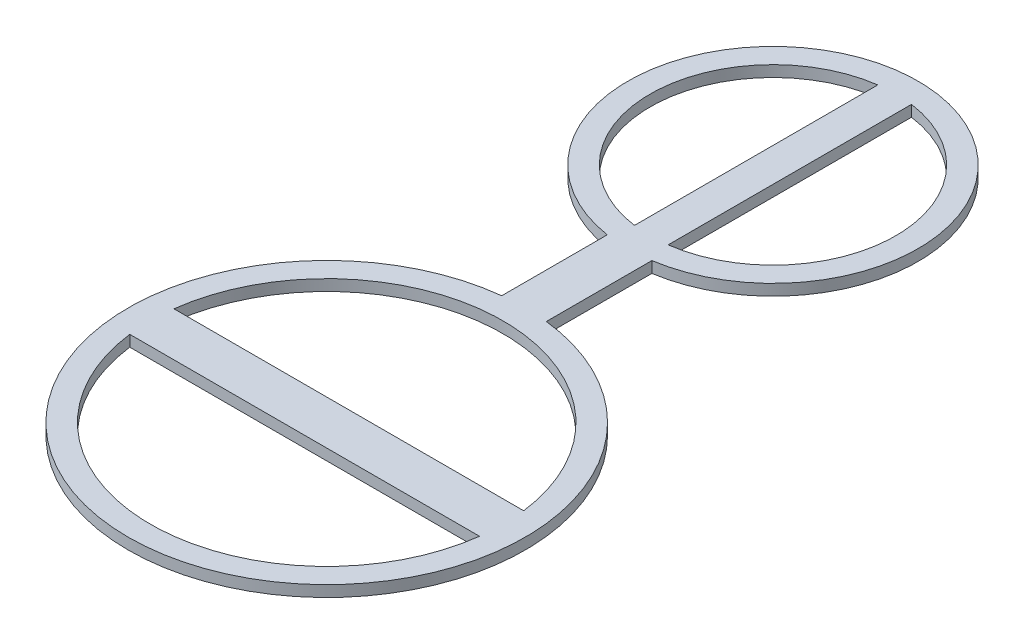
SolidWorks part; units mm, degrees
ref_plane "Front Plane" through (0, 0, 0) normal (0, 0, 1) x (1, 0, 0)
ref_plane "Top Plane" through (0, 0, 0) normal (0, 1, 0) x (1, 0, 0)
ref_plane "Right Plane" through (0, 0, 0) normal (1, 0, 0) x (0, 0, -1)
sketch "Sketch1" plane through (0, 0, 0) normal (0, 1, 0) x (1, 0, 0)
  line L0 (0, 0) -> (79, 0) construction
  line L1 (0, 0) -> (-79, 0) construction
  line L2 (0, 9.9) -> (79, 9.9)
  line L3 (0, 9.9) -> (-79, 9.9)
  line L4 (0, -9.9) -> (79, -9.9)
  line L5 (0, -9.9) -> (-79, -9.9)
  line L6 (0, 0) -> (0, 200) construction
  line L7 (55, 200) -> (-55, 200) construction
  line L8 (-7.55, 255) -> (-7.55, 145)
  line L9 (7.55, 255) -> (7.55, 145)
  line L10 (0, 89) -> (0, 135) construction
  line L11 (10, 88.4364) -> (10, 135)
  line L12 (-10, 88.4364) -> (-10, 135)
  line L13 (-10, 89) -> (-10, 135) construction
  line L14 (10, 89) -> (10, 135) construction
  line L15 (-10, 135) -> (-10, 135.7232)
  line L16 (10, 135) -> (10, 135.7232)
  arc A0 (-78.3772, -9.9) -> (78.3772, -9.9) centre (0, 0) ccw
  circle A1 centre (0, 0) radius 89
  circle A2 centre (0, 0) radius 79 construction
  arc A3 (78.3772, 9.9) -> (-78.3772, 9.9) centre (0, 0) ccw
  arc A4 (7.55, 145.4702) -> (7.55, 254.5298) centre (0, 200) ccw
  arc A5 (10, 135.7232) -> (-10, 135.7232) centre (0, 200) ccw
  arc A8 (-7.55, 254.5298) -> (-7.55, 145.4702) centre (0, 200) ccw
  dimension "D1" = 158
  dimension "D6" = 110.1
  dimension "D5" = 200
  dimension "D2" = 9.9
  dimension "D3" = 9.9
  dimension "D4" = 10
  dimension "D10" = 10
  dimension "D11" = 10
extrude "Boss-Extrude1" add sketch "Sketch1" along normal blind 5
